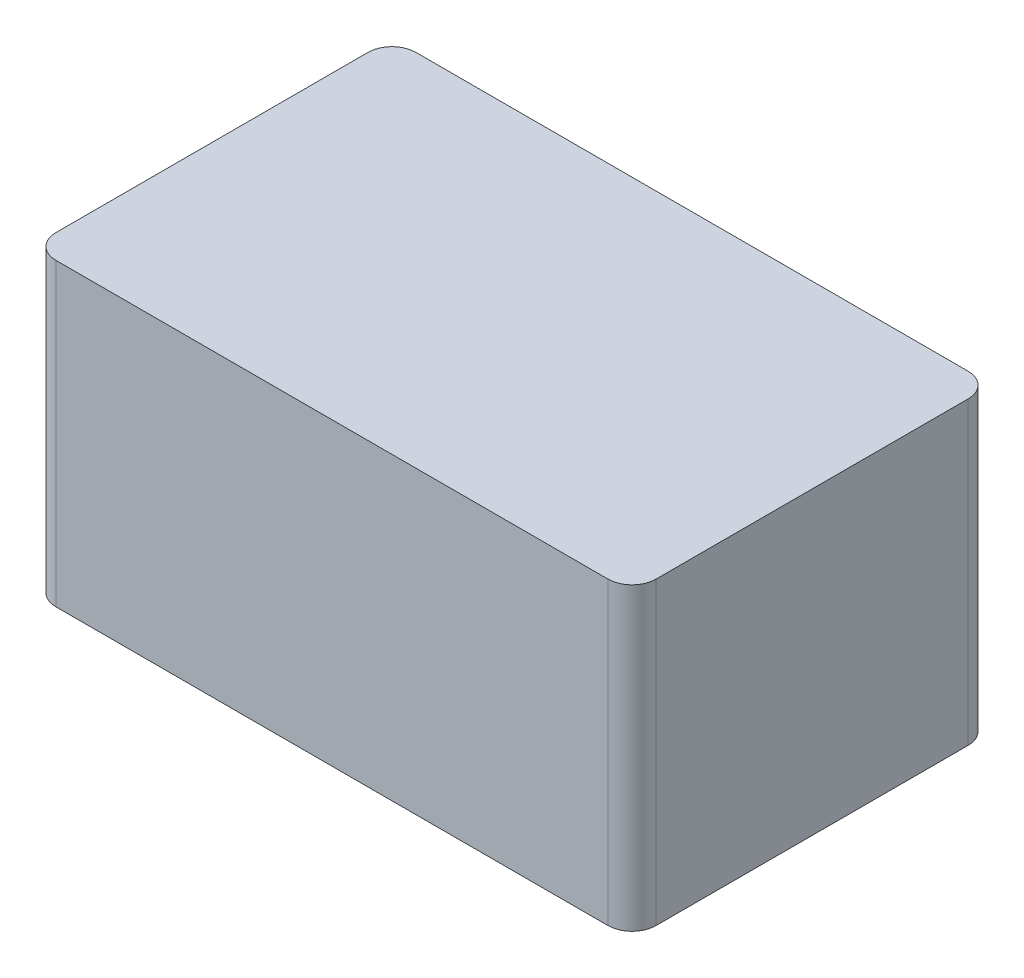
SolidWorks part; units mm, degrees
ref_plane "前视基准面" through (0, 0, 0) normal (0, 0, 1) x (1, 0, 0)
ref_plane "上视基准面" through (0, 0, 0) normal (0, 1, 0) x (1, 0, 0)
ref_plane "右视基准面" through (0, 0, 0) normal (1, 0, 0) x (0, 0, -1)
sketch "草图1" plane through (0, 0, 0) normal (0, 1, 0) x (1, 0, 0)
  line L1 (25, -15) -> (-25, -15)
  line L2 (25, -15) -> (25, 15)
  line L3 (25, 15) -> (-25, 15)
  line L4 (-25, -15) -> (-25, 15)
  line L5 (25, -15) -> (-25, 15) construction
  line L6 (25, 15) -> (-25, -15) construction
  point P0 (0, 0)
extrude "凸台-拉伸1" add sketch "草图1" along normal blind 25
fillet "圆角1" radius 2 4 edges at (-25, 12.5, -15) (-25, 12.5, 15) (25, 12.5, -15) (25, 12.5, 15)
